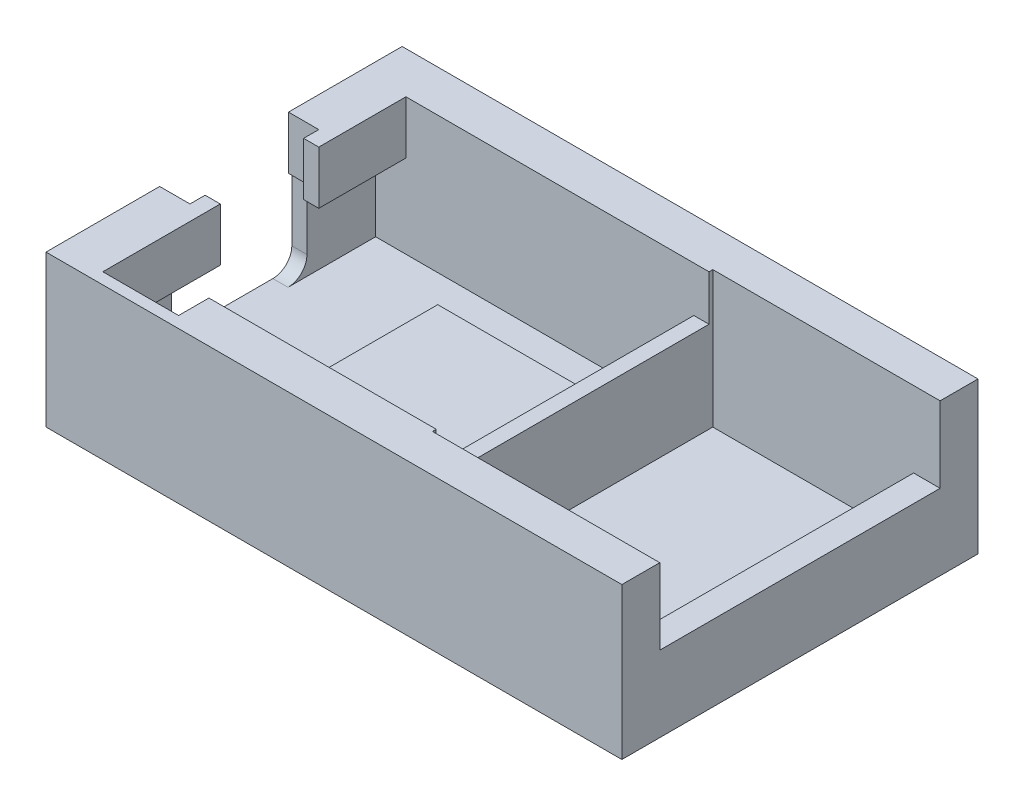
SolidWorks part; units mm, degrees
ref_plane "Front Plane" through (0, 0, 0) normal (0, 0, 1) x (1, 0, 0)
ref_plane "Top Plane" through (0, 0, 0) normal (0, 1, 0) x (1, 0, 0)
ref_plane "Right Plane" through (0, 0, 0) normal (1, 0, 0) x (0, 0, -1)
sketch "Sketch1" plane through (0, 0, 0) normal (0, 1, 0) x (1, 0, 0)
  line L1 (0, 0) -> (40, 0)
  line L2 (0, 0) -> (0, 24)
  line L3 (0, 24) -> (40, 24)
  line L4 (40, 0) -> (40, 24)
  dimension "D1" = 24
  dimension "D2" = 40
extrude "Boss-Extrude1" add sketch "Sketch1" along normal blind 1
sketch "Sketch2" plane through (0, 1, 0) normal (0, 1, 0) x (1, 0, 0)
  line L1 (0, 24) -> (40, 24)
  line L2 (0, 24) -> (0, 0)
  line L3 (0, 0) -> (40, 0)
  line L4 (40, 24) -> (40, 0)
  line L5 (1, 20.75) -> (22, 20.75)
  line L6 (1, 20.75) -> (1, 3.25)
  line L7 (1, 3.25) -> (22, 3.25)
  line L8 (22, 20.75) -> (22, 3.25)
  line L9 (23, 21.25) -> (36, 21.25)
  line L10 (23, 21.25) -> (23, 2.75)
  line L11 (23, 2.75) -> (36, 2.75)
  line L12 (36, 21.25) -> (36, 2.75)
  dimension "D1" = 17.5
  dimension "D2" = 21
  dimension "D3" = 3.25
  dimension "D4" = 1
  dimension "D5" = 18.5
  dimension "D6" = 13
  dimension "D7" = 1
  dimension "D8" = 2.75
extrude "Boss-Extrude3" add sketch "Sketch2" along normal blind 9
sketch "Sketch3" plane through (0, 10, 0) normal (0, 1, 0) x (1, 0, 0)
  line L0 (22, 20.75) -> (23, 20.75)
  line L1 (23, 21.25) -> (23, 2.75) construction
  line L2 (22, 20.75) -> (22, 3.25)
  line L3 (22, 3.25) -> (23, 3.25)
  line L4 (23, 21.25) -> (23, 2.75) construction
  line L5 (23, 3.25) -> (23, 20.75)
extrude "Cut-Extrude2" cut sketch "Sketch3" against normal blind 3
sketch "Sketch4" plane through (0, 1, 0) normal (0, 1, 0) x (1, 0, 0)
  line L0 (22, 20.75) -> (22, 3.25) construction
  line L1 (8.14, 17.96) -> (18.38, 17.96)
  line L2 (8.14, 17.96) -> (8.14, 6.04)
  line L3 (8.14, 6.04) -> (18.38, 6.04)
  line L4 (18.38, 17.96) -> (18.38, 6.04)
  line L5 (22, 20.75) -> (1, 20.75) construction
  line L6 (1, 3.25) -> (22, 3.25) construction
  line L7 (1, 20.75) -> (1, 3.25) construction
  dimension "D1" = 3.62
  dimension "D2" = 2.79
  dimension "D3" = 2.79
  dimension "D4" = 7.14
extrude "Boss-Extrude4" add sketch "Sketch4" along normal blind 1.21
sketch "Sketch5" plane through (1, 0, 0) normal (1, 0, 0) x (0, 0, -1)
  line L0 (7.53, 2.25) -> (7.53, 2.96)
  line L1 (8.78, 1) -> (15.22, 1)
  line L3 (16.47, 2.96) -> (16.47, 2.25)
  line L4 (20.75, 1) -> (3.25, 1) construction
  line L5 (3.25, 10) -> (3.25, 1) construction
  line L6 (7.53, 2.96) -> (7.53, 10)
  line L7 (20.75, 10) -> (3.25, 10) construction
  line L8 (7.53, 10) -> (16.47, 10)
  line L9 (16.47, 10) -> (16.47, 2.96)
  line L10 (20.75, 10) -> (20.75, 1) construction
  arc A0 (7.53, 2.25) -> (8.78, 1) centre (8.78, 2.25) ccw
  arc A3 (15.22, 1) -> (16.47, 2.25) centre (15.22, 2.25) ccw
  dimension "D7" = 1.25
  dimension "D1" = 1.25
  dimension "D2" = 0.71
  dimension "D3" = 6.44
  dimension "D4" = 4.28
  dimension "D9" = 0.71
  dimension "D10" = 4.28
extrude "Cut-Extrude3" cut sketch "Sketch5" against normal blind 2
sketch "Sketch8" plane through (0, 10, 0) normal (0, 1, 0) x (1, 0, 0)
  line L0 (36, 21.25) -> (40, 21.25)
  line L1 (40, 0) -> (40, 24) construction
  line L2 (36, 2.75) -> (40, 2.75)
  line L3 (40, 2.75) -> (40, 21.25)
  line L4 (36, 21.25) -> (36, 2.75)
extrude "Cut-Extrude4" cut sketch "Sketch8" against normal blind 5
sketch "Sketch10" plane through (0, 10, 0) normal (0, 1, 0) x (1, 0, 0)
sketch "Sketch11" plane through (40, 0, 0) normal (1, 0, 0) x (0, 0, -1)
  line L0 (21.25, 10) -> (24, 10) construction
  line L1 (0, 0) -> (24, 0)
  line L2 (0, 0) -> (0, 10)
  line L3 (0, 10) -> (24, 10)
  line L4 (24, 0) -> (24, 10)
  line L5 (24, 10) -> (24, 0) construction
extrude "Cut-Extrude5" cut sketch "Sketch11" against normal blind 2
sketch "Sketch12" plane through (0, 10, 0) normal (0, 1, 0) x (1, 0, 0)
  line L0 (0, 24) -> (0, 16.47) construction
  line L1 (4, 1) -> (8, 1)
  line L2 (4, 1) -> (4, 4)
  line L3 (4, 4) -> (8, 4)
  line L4 (8, 1) -> (8, 4)
  line L5 (0, 0) -> (38, 0) construction
  dimension "D1" = 4
  dimension "D2" = 1
  dimension "D3" = 3
  dimension "D4" = 4
extrude "Cut-Extrude6" cut sketch "Sketch12" against normal blind 3
sketch "Sketch13" plane through (0, 10, 0) normal (0, 1, 0) x (1, 0, 0)
  line L0 (23, 20.75) -> (1, 20.75) construction
  line L2 (1, 16.47) -> (1, 20.75)
  line L3 (1, 20.75) -> (3, 20.75)
  line L5 (3, 20.75) -> (3, 15.25)
  line L8 (1, 3.25) -> (3, 3.25)
  line L10 (1, 3.25) -> (4, 3.25) construction
  line L14 (2, 7.75) -> (0, 7.75)
  line L16 (0, 16.47) -> (1, 16.47)
  line L17 (0, 16.47) -> (0, 16.25)
  line L18 (0, 16.25) -> (2, 16.25)
  line L21 (0, 7.75) -> (0, 7.53)
  line L22 (1, 7.53) -> (1, 3.25)
  line L23 (0, 7.53) -> (1, 7.53)
  line L26 (3, 15.25) -> (2, 15.25)
  line L27 (2, 16.25) -> (2, 15.25)
  line L30 (3, 8.75) -> (2, 8.75)
  line L31 (2, 7.75) -> (2, 8.75)
  line L32 (3, 8.75) -> (3, 3.25)
  dimension "D1" = 0.22
  dimension "D2" = 0.22
  dimension "D3" = 2
  dimension "D4" = 2
  dimension "D5" = 1
  dimension "D6" = 1
  dimension "D7" = 1
  dimension "D8" = 1
extrude "Boss-Extrude5" add sketch "Sketch13" against normal blind 3.5
sketch "Sketch14" plane through (0, 10, 0) normal (0, 1, 0) x (1, 0, 0)
  line L1 (4, 1) -> (3, 1)
  line L2 (4, 1) -> (4, 3.25)
  line L3 (4, 3.25) -> (3, 3.25)
  line L4 (3, 1) -> (3, 3.25)
extrude "Cut-Extrude7" cut sketch "Sketch14" against normal blind 3
sketch "Sketch15" plane through (0, 0, -24) normal (0, 0, -1) x (-1, 0, 0)
  line L1 (-38, 0) -> (0, 0)
  line L2 (-38, 0) -> (-38, 10)
  line L3 (-38, 10) -> (0, 10)
  line L4 (0, 0) -> (0, 10)
extrude "Cut-Extrude8" cut sketch "Sketch15" against normal blind 0.25
sketch "Sketch16" plane through (0, 0, 0) normal (0, 0, 1) x (1, 0, 0)
  line L1 (0, 0) -> (38, 0)
  line L2 (0, 0) -> (0, 10)
  line L3 (0, 10) -> (38, 10)
  line L4 (38, 0) -> (38, 10)
extrude "Cut-Extrude9" cut sketch "Sketch16" against normal blind 0.25
sketch "Sketch17" plane through (36, 0, 0) normal (-1, 0, 0) x (0, 0, 1)
  line L1 (-21.25, 1) -> (-2.75, 1)
  line L2 (-21.25, 1) -> (-21.25, 5)
  line L3 (-21.25, 5) -> (-2.75, 5)
  line L4 (-2.75, 1) -> (-2.75, 5)
extrude "Cut-Extrude10" cut sketch "Sketch17" against normal blind 0.25
sketch "Sketch18" plane through (0, 0, -3.25) normal (0, 0, -1) x (-1, 0, 0)
  line L0 (-1, 1) -> (-1, 6.484)
  line L1 (-1, 6.5) -> (-1, 1) construction
  line L2 (-1, 6.484) -> (-3, 6.5)
  line L3 (-3, 6.5) -> (-3, 7)
  line L4 (-3, 7) -> (-8, 7)
  line L5 (-22, 7) -> (-22, 1)
  line L6 (-22, 1) -> (-1, 1)
  line L8 (-23, 7) -> (-22, 7)
  line L9 (-23, 7) -> (-23, 10)
  line L10 (-23, 10) -> (-8, 10)
  line L11 (-8, 7) -> (-8, 10)
extrude "Cut-Extrude11" cut sketch "Sketch18" against normal blind 0.25
sketch "Sketch19" plane through (0, 0, -20.75) normal (0, 0, 1) x (1, 0, 0)
  line L0 (1, 1) -> (1, 6.5)
  line L1 (1, 6.5) -> (1, 1) construction
  line L2 (1, 6.5) -> (3, 6.5)
  line L3 (3, 6.5) -> (3, 10)
  line L4 (3, 10) -> (23, 10)
  line L5 (23, 10) -> (23, 7)
  line L6 (23, 7) -> (22, 7)
  line L7 (22, 7) -> (22, 1)
  line L8 (22, 1) -> (1, 1)
extrude "Cut-Extrude12" cut sketch "Sketch19" against normal blind 0.25
